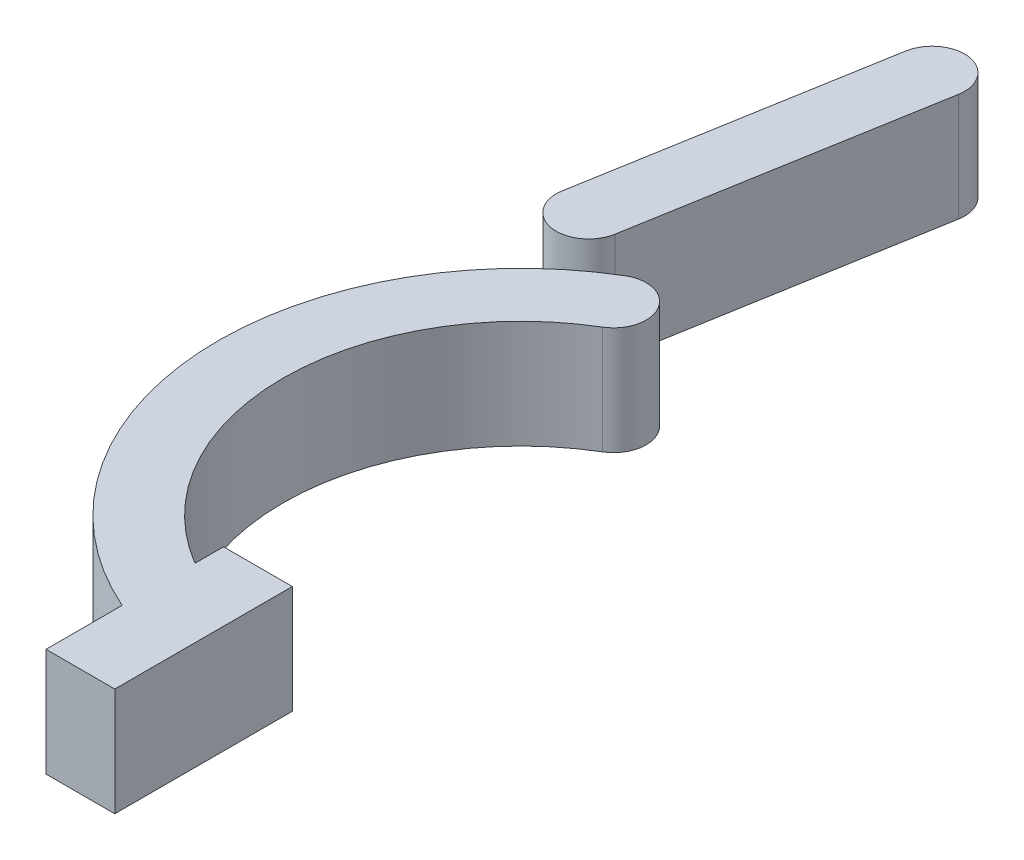
SolidWorks part; units mm, degrees
ref_plane "Front Plane" through (0, 0, 0) normal (0, 0, 1) x (1, 0, 0)
ref_plane "Top Plane" through (0, 0, 0) normal (0, 1, 0) x (1, 0, 0)
ref_plane "Right Plane" through (0, 0, 0) normal (1, 0, 0) x (0, 0, -1)
sketch "Sketch1" plane through (0, 0, 0) normal (0, 1, 0) x (1, 0, 0)
  line L0 (0, 25.9924) -> (0, -34.0076) construction
  line L1 (36.0394, 1.5) -> (-36.0394, 1.5)
  line L2 (36.0394, 1.5) -> (36.0394, -1.5)
  line L3 (36.0394, -1.5) -> (-36.0394, -1.5)
  line L4 (-36.0394, 1.5) -> (-36.0394, -1.5)
  line L5 (36.0394, 1.5) -> (-36.0394, -1.5) construction
  line L6 (36.0394, -1.5) -> (-36.0394, 1.5) construction
  line L7 (3, 25.9924) -> (3, -34.0076)
  line L8 (-3, 25.9924) -> (-3, -34.0076)
  line L9 (-12.5, -7.4123) -> (-17.185, -34.5103) construction
  line L10 (-9.5439, -7.9234) -> (-14.2289, -35.0214)
  line L11 (-15.4561, -6.9012) -> (-20.1412, -33.9992)
  line L12 (0, 0) -> (0, -22.5881) construction
  line L13 (-11.4778, -1.5) -> (-11.9889, -4.4561)
  line L14 (-6.4742, -38.707) -> (-2.4278, -35.7699) construction
  line L15 (-17.175, -37.5102) -> (-17.1551, -43.5102) construction
  line L17 (-7.289, -78.1854) -> (-0.9261, -78.1854)
  line L18 (-7.289, -78.1854) -> (-7.289, -94.6121)
  line L19 (-7.289, -94.6121) -> (-0.9261, -94.6121)
  line L20 (-0.9261, -78.1854) -> (-0.9261, -94.6121)
  arc A0 (3, 25.9924) -> (-3, 25.9924) centre (0, 25.9924) ccw
  arc A1 (-3, -34.0076) -> (3, -34.0076) centre (0, -34.0076) ccw
  arc A2 (-9.5439, -7.9234) -> (-15.4561, -6.9012) centre (-12.5, -7.4123) ccw
  arc A3 (-20.1412, -33.9992) -> (-14.2289, -35.0214) centre (-17.185, -34.5103) ccw
  arc A4 (-8.9021, -40.4693) -> (-4.786, -85.3405) centre (3.9461, -61.9151) ccw construction
  arc A5 (-10.4438, -37.8958) -> (-5.8339, -88.1515) centre (3.9461, -61.9151) ccw
  arc A6 (-7.3603, -43.0428) -> (-3.7382, -82.5294) centre (3.9461, -61.9151) ccw
  arc A7 (-7.3603, -43.0428) -> (-10.4438, -37.8958) centre (-8.9021, -40.4693) ccw
  arc A8 (-5.8339, -88.1515) -> (-3.7382, -82.5294) centre (-4.786, -85.3405) ccw
  point P0 (0, 0)
  point P8 (0, -4.0076)
  point P13 (-14.8425, -20.9613)
  point P27 (-20.9493, -64.1987)
  point P34 (-7.289, -77.2114)
  point P35 (-0.9261, -94.6121)
  dimension "D3" = 3
  dimension "D10" = 25
  dimension "D1" = 3
  dimension "D2" = 27.5
  dimension "D4" = 5
  dimension "D6" = 12.5
  dimension "D7" = 6
  dimension "D8" = 3
  dimension "D9" = 60
  dimension "D11" = 170
  dimension "D12" = 8.75
  dimension "D13" = 128.63
extrude "Boss-Extrude1" add sketch "Sketch1" along normal mid plane 10 contours A8 A5 L18 L19 L20 L17 A6 | L11 A3 L10 A2
